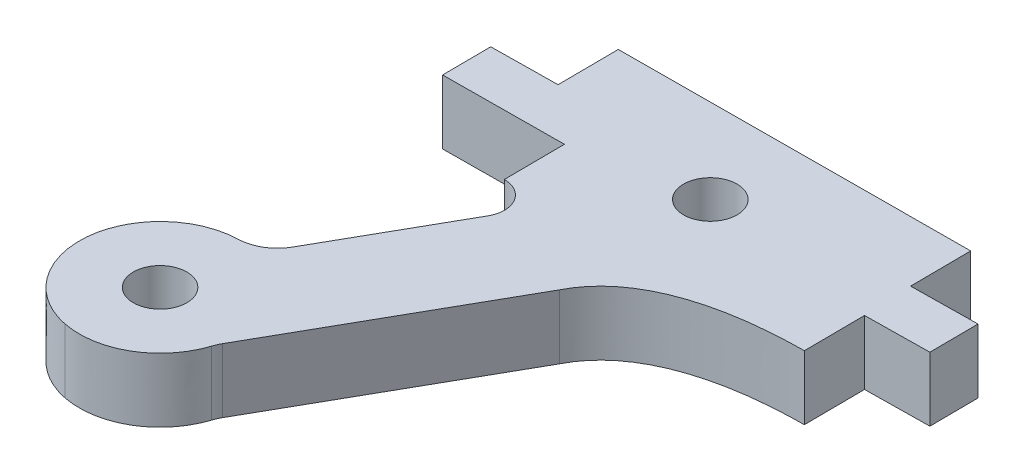
SolidWorks part; units mm, degrees
material "Acrylic (Medium-high impact)"
ref_plane "Front Plane" through (0, 0, 0) normal (0, 0, 1) x (1, 0, 0)
ref_plane "Top Plane" through (0, 0, 0) normal (0, 1, 0) x (1, 0, 0)
ref_plane "Right Plane" through (0, 0, 0) normal (1, 0, 0) x (0, 0, -1)
sketch "Sketch1" plane through (0, 0, 0) normal (0, 1, 0) x (1, 0, 0)
  line L0 (-5.7665, 10.4368) -> (-5.7634, 10.4368)
  line L1 (-5.7634, 10.4368) -> (-5.7415, 7.4368)
  line L2 (-5.7415, 7.4368) -> (-5.7415, 7.4346)
  line L3 (-5.7415, 7.4346) -> (-9.0353, 7.3928)
  line L4 (-9.0353, 7.3928) -> (-9.0178, 4.9929)
  line L5 (-9.0178, 4.9929) -> (-3.0286, 5.0368)
  line L6 (-3.0286, 5.0368) -> (-3.0069, 2.0366)
  line L7 (-1.8541, 0.0701) -> (-5.3519, -6.1032)
  line L8 (-2.9451, -11.9842) -> (3.0881, -1.3361)
  line L9 (14.9389, 5.1687) -> (14.9213, 7.5686)
  line L10 (14.9213, 7.5686) -> (11.6275, 7.5247)
  line L11 (11.6275, 7.5247) -> (11.6056, 10.5246)
  line L12 (11.6056, 10.5246) -> (-5.7665, 10.4368)
  line L13 (3.8801, 7.2246) -> (2.0233, 5.337) construction
  line L14 (-7.8457, -10.1832) -> (-5.9617, -12.0432) construction
  circle A0 centre (2.9517, 6.2808) radius 1.3239
  circle A1 centre (-6.9037, -11.1132) radius 1.3237
  spline S0 degree 3 poles (-3.0069, 2.0366) (-2.5372, 2.0403) (-2.1015, 1.7925) (-1.8637, 1.3868) knots 7 7 7 7 8 8 8 8
  spline S1 degree 3 poles (-1.8637, 1.3868) (-1.6259, 0.9813) (-1.6223, 0.4793) (-1.8541, 0.0701) knots 8 8 8 8 9 9 9 9
  spline S2 degree 3 poles (-5.3519, -6.1032) (-5.6958, -6.7101) (-6.3304, -7.0935) (-7.0267, -7.115) knots 10 10 10 10 11 11 11 11
  spline S3 degree 3 poles (-7.0267, -7.115) (-9.0533, -7.1776) (-10.7114, -8.7519) (-10.8824, -10.7759) knots 11 11 11 11 12 12 12 12
  spline S4 degree 3 poles (-10.8824, -10.7759) (-11.0532, -12.8) (-9.683, -14.631) (-7.6956, -15.0339) knots 12 12 12 12 13 13 13 13
  spline S5 degree 3 poles (-7.6956, -15.0339) (-5.7083, -15.4367) (-3.7351, -14.2837) (-3.1072, -12.3522) knots 13 13 13 13 14 14 14 14
  spline S6 degree 3 poles (-3.1072, -12.3522) (-3.0655, -12.2244) (-3.0113, -12.1013) (-2.9451, -11.9842) knots 14 14 14 14 15 15 15 15
  spline S7 degree 3 poles (3.0881, -1.3361) (4.6436, 1.7578) (9.3293, 2.1068) (11.7668, 2.1246) knots 16 16 16 16 17 17 17 17
  spline S8 degree 2 poles (11.7668, 2.1246) (11.7449, 5.1248) (11.7452, 5.1248) knots 17 17 17 18 18 18
  spline S9 degree 2 poles (11.7452, 5.1248) (11.7456, 5.1248) (14.9389, 5.1687) knots 18 18 18 19 19 19
extrude "Boss-Extrude1" add sketch "Sketch1" along normal blind 3.175
